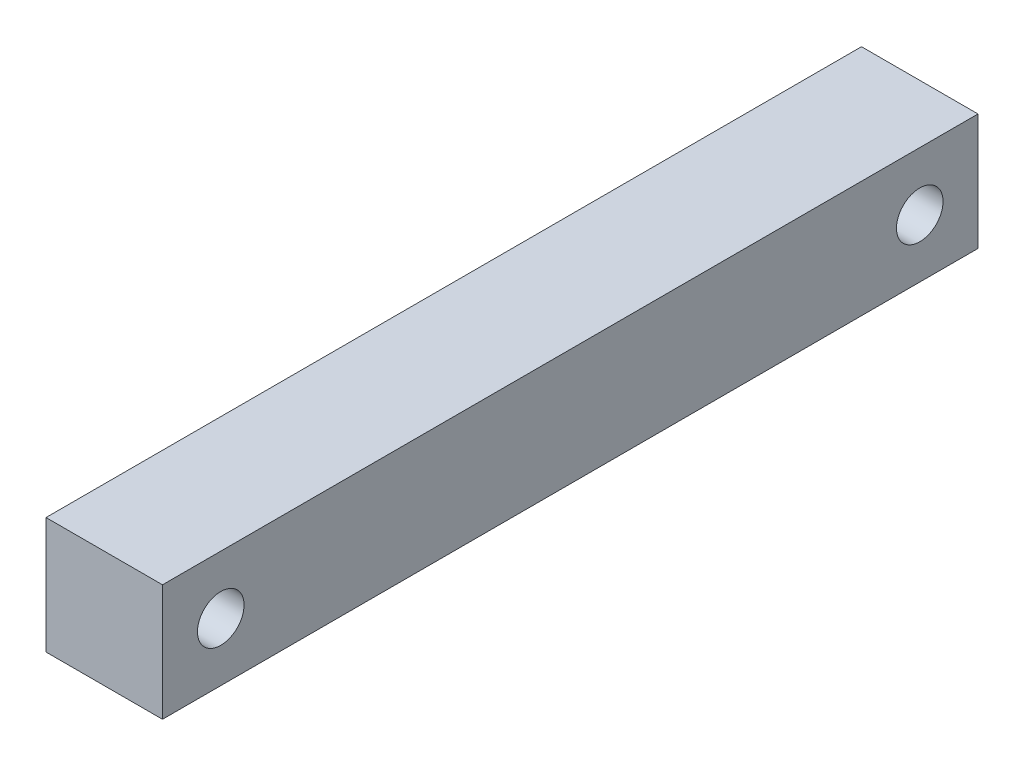
SolidWorks part; units mm, degrees
ref_plane "Front Plane" through (0, 0, 0) normal (0, 0, 1) x (1, 0, 0)
ref_plane "Top Plane" through (0, 0, 0) normal (0, 1, 0) x (1, 0, 0)
ref_plane "Right Plane" through (0, 0, 0) normal (1, 0, 0) x (0, 0, -1)
sketch "Sketch1" plane through (0, 0, 0) normal (0, 1, 0) x (1, 0, 0)
  line L1 (-2.5, 17.5) -> (2.5, 17.5)
  line L2 (-2.5, 17.5) -> (-2.5, -17.5)
  line L3 (-2.5, -17.5) -> (2.5, -17.5)
  line L4 (2.5, 17.5) -> (2.5, -17.5)
  line L5 (-2.5, 17.5) -> (2.5, -17.5) construction
  line L6 (-2.5, -17.5) -> (2.5, 17.5) construction
  point P0 (0, 0)
  dimension "D1" = 35
  dimension "D2" = 5
extrude "Boss-Extrude1" add sketch "Sketch1" along normal blind 5
sketch "Sketch2" plane through (2.5, 0, 0) normal (1, 0, 0) x (0, 0, -1)
  line L0 (17.5, 2.5) -> (0, 2.5) construction
  line L1 (17.5, 5) -> (17.5, 0) construction
  line L2 (15, 5) -> (15, 0) construction
  line L3 (-17.5, 5) -> (17.5, 5) construction
  line L4 (-17.5, 0) -> (17.5, 0) construction
  circle A0 centre (15, 2.5) radius 1
  dimension "D2" = 2
  dimension "D1" = 2.5
extrude "Cut-Extrude1" cut sketch "Sketch2" against normal through all
mirror "Mirror1" about plane through (0, 0, 0) normal (0, 0, 1) of "Cut-Extrude1"
